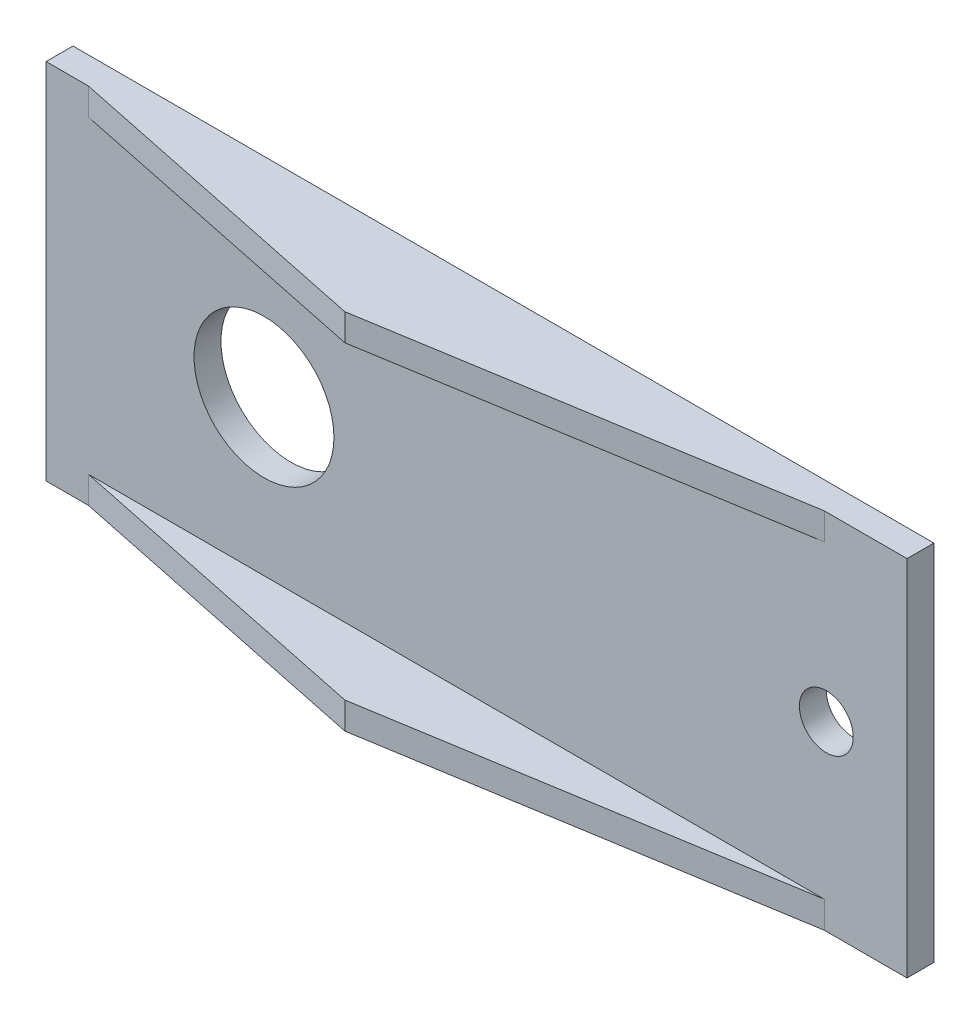
SolidWorks part; units mm, degrees
ref_plane "Alzado" through (0, 0, 0) normal (0, 0, 1) x (1, 0, 0)
ref_plane "Planta" through (0, 0, 0) normal (0, 1, 0) x (1, 0, 0)
ref_plane "Vista lateral" through (0, 0, 0) normal (1, 0, 0) x (0, 0, -1)
sketch "Croquis1" plane through (0, 0, 0) normal (0, 0, 1) x (1, 0, 0)
  line L0 (0, -6.75) -> (32, -6.75) construction
  line L1 (0, 0) -> (32, 0)
  line L2 (0, 0) -> (0, -13.5)
  line L3 (0, -13.5) -> (32, -13.5)
  line L4 (32, 0) -> (32, -13.5)
  circle A0 centre (8.1, -6.75) radius 2.6
  circle A1 centre (29, -6.75) radius 1
  point P11 (5.5, -6.75)
  point P12 (30, -6.75)
  dimension "D3" = 5.2
  dimension "D4" = 2
  dimension "D1" = 32
  dimension "D2" = 13.5
  dimension "D5" = 5.5
  dimension "D6" = 2
extrude "Saliente-Extruir1" add sketch "Croquis1" along normal blind 1
sketch "Croquis2" plane through (0, 0, 0) normal (0, 1, 0) x (1, 0, 0)
  line L0 (1.5715, -1) -> (13.6061, -3.5)
  line L1 (32, -1) -> (0, -1) construction
  line L2 (13.6061, -3.5) -> (28.9267, -1)
  line L3 (32, 0) -> (0, 0) construction
  line L4 (1.5715, -1) -> (28.9267, -1)
  dimension "D1" = 3.5
extrude "Saliente-Extruir2" add sketch "Croquis2" against normal blind 1
ref_plane "Plano1" through (0, -6.75, 0) normal (0, 1, 0) x (1, 0, 0)
mirror "Simetría1" about plane through (0, -6.75, 0) normal (0, 1, 0) of "Saliente-Extruir2"
